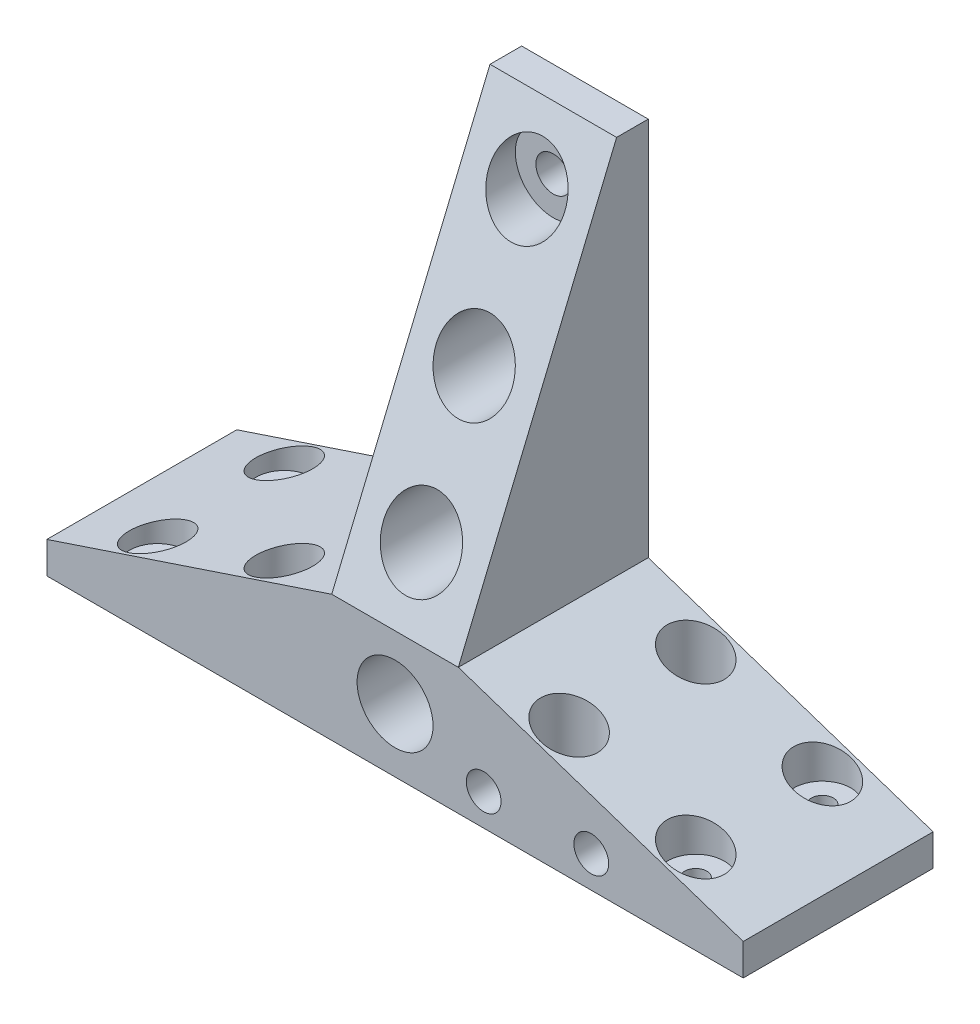
SolidWorks part; units mm, degrees
ref_plane "Plan de face" through (0, 0, 0) normal (0, 0, 1) x (1, 0, 0)
ref_plane "Plan de dessus" through (0, 0, 0) normal (0, 1, 0) x (1, 0, 0)
ref_plane "Plan de droite" through (0, 0, 0) normal (1, 0, 0) x (0, 0, -1)
sketch "Esquisse1" plane through (0, 0, 0) normal (0, 0, 1) x (1, 0, 0)
  line L1 (-9.5845, 32.7642) -> (10.4155, 32.7642)
  line L2 (-9.5845, 32.7642) -> (-9.5845, -47.2358)
  line L3 (-9.5845, -47.2358) -> (10.4155, -47.2358)
  line L4 (10.4155, 32.7642) -> (10.4155, -47.2358)
  circle A0 centre (0.4155, 22.7642) radius 2.75
  circle A1 centre (0.4155, -17.2358) radius 2.75
  circle A2 centre (0.4155, 2.7642) radius 2.75
  circle A3 centre (0.4155, -37.2358) radius 2.75
  point P13 (0.4155, -47.2358)
  dimension "D3" = 5.5
  dimension "D1" = 20
  dimension "D2" = 80
  dimension "D4" = 10
  dimension "D5" = 20
  dimension "D6" = 10
  dimension "D7" = 20
extrude "Boss.-Extru.1" add sketch "Esquisse1" along normal blind 5
sketch "Esquisse3" plane through (0, 0, 5) normal (0, 0, 1) x (1, 0, 0)
  line L0 (-9.5845, -47.2358) -> (-54.5845, -47.2358)
  line L1 (-54.5845, -47.2358) -> (-54.5845, -42.2358)
  line L2 (-54.5845, -42.2358) -> (-9.5845, -27.2358)
  line L3 (-9.5845, 32.7642) -> (-9.5845, -47.2358) construction
  line L4 (-9.5845, -27.2358) -> (-9.5845, -47.2358)
  line L5 (10.4155, -47.2358) -> (55.4155, -47.2358)
  line L6 (55.4155, -47.2358) -> (55.4155, -42.2358)
  line L7 (55.4155, -42.2358) -> (10.4155, -27.2358)
  line L8 (10.4155, -47.2358) -> (10.4155, 32.7642) construction
  line L9 (10.4155, -27.2358) -> (10.4155, -47.2358)
  dimension "D1" = 5
  dimension "D2" = 45
  dimension "D3" = 20
extrude "Boss.-Extru.2" add sketch "Esquisse3" against normal blind 5
sketch "Esquisse4" plane through (0, 0, 5) normal (0, 0, 1) x (1, 0, 0)
  line L0 (55.4155, -47.2358) -> (55.4155, -42.2358) construction
  line L1 (55.4155, -42.2358) -> (10.4155, -27.2358) construction
  line L2 (-9.5845, -27.2358) -> (-54.5845, -42.2358) construction
  line L3 (-54.5845, -42.2358) -> (-54.5845, -47.2358) construction
  line L4 (-54.5845, -47.2358) -> (55.4155, -47.2358) construction
  line L5 (55.4155, -47.2358) -> (55.4155, -42.2358)
  line L6 (55.4155, -42.2358) -> (10.4155, -27.2358)
  line L7 (-9.5845, -27.2358) -> (-54.5845, -42.2358)
  line L8 (-54.5845, -42.2358) -> (-54.5845, -47.2358)
  line L9 (-54.5845, -47.2358) -> (55.4155, -47.2358)
  line L10 (-9.5845, -27.2358) -> (10.4155, -27.2358)
  circle A0 centre (0.4155, -37.2358) radius 2.75 construction
  circle A1 centre (0.4155, -37.2358) radius 2.75
extrude "Boss.-Extru.3" add sketch "Esquisse4" along normal blind 25
sketch "Esquisse5" plane through (-9.5845, 0, 0) normal (-1, 0, 0) x (0, 0, 1)
  line L0 (5, -27.2358) -> (30, -27.2358)
  line L1 (30, -27.2358) -> (5, 32.7642)
  line L2 (5, 32.7642) -> (5, -27.2358)
extrude "Boss.-Extru.4" add sketch "Esquisse5" against normal up to surface (20 mm away) up to face at (10.4155, 2.7642, 2.5)
sketch "Esquisse6" plane through (0, 0, 5) normal (0, 0, -1) x (-1, 0, 0)
  circle A0 centre (-0.4155, 2.7642) radius 6
  circle A1 centre (-0.4155, -17.2358) radius 6
  circle A2 centre (-0.4155, 22.7642) radius 6
  circle A3 centre (-0.4155, -37.2358) radius 6
  dimension "D1" = 12
extrude "Enlèv. mat.-Extru.1" cut sketch "Esquisse6" against normal up to next
sketch "Esquisse7" plane through (0, -47.2358, 0) normal (0, -1, 0) x (1, 0, 0)
  line L0 (-42.0845, 25) -> (-22.0845, 25) construction
  line L1 (-22.0845, 25) -> (-22.0845, 5) construction
  line L2 (-54.5845, 0) -> (-54.5845, 30) construction
  line L3 (22.9155, 5) -> (22.9155, 25) construction
  line L4 (22.9155, 25) -> (42.9155, 25) construction
  line L5 (55.4155, 0) -> (55.4155, 30) construction
  circle A0 centre (-42.0845, 25) radius 1.75
  circle A1 centre (-22.0845, 25) radius 1.75
  circle A2 centre (-22.0845, 5) radius 1.75
  circle A3 centre (-42.0845, 5) radius 1.75
  circle A4 centre (42.9155, 25) radius 1.75
  circle A5 centre (42.9155, 5) radius 1.75
  circle A6 centre (22.9155, 5) radius 1.75
  circle A7 centre (22.9155, 25) radius 1.75
  point P8 (-22.0845, 15)
  point P11 (-54.5845, 15)
  point P12 (-32.0845, 25)
  point P21 (22.9155, 15)
  point P24 (55.4155, 15)
  point P25 (32.9155, 25)
  dimension "D1" = 3.5
  dimension "D4" = 3.5
  dimension "D2" = 20
  dimension "D3" = 22.5
  dimension "D5" = 20
  dimension "D6" = 22.5
extrude "Enlèv. mat.-Extru.2" cut sketch "Esquisse7" against normal up to next
ref_plane "Plan3" through (0, -42.2358, 0) normal (0, -1, 0) x (-1, 0, 0)
sketch "Esquisse9" plane through (0, -42.2358, 0) normal (0, -1, 0) x (-1, 0, 0)
  circle A0 centre (42.0845, -25) radius 4.5
  circle A1 centre (22.0845, -25) radius 4.5
  circle A2 centre (22.0845, -5) radius 4.5
  circle A3 centre (42.0845, -5) radius 4.5
  circle A4 centre (-22.9155, -25) radius 4.5
  circle A5 centre (-42.9155, -25) radius 4.5
  circle A6 centre (-42.9155, -5) radius 4.5
  circle A7 centre (-22.9155, -5) radius 4.5
  dimension "D1" = 9
extrude "Enlèv. mat.-Extru.3" cut sketch "Esquisse9" against normal up to next
sketch "Esquisse10" plane through (0, 0, 30) normal (0, 0, 1) x (1, 0, 0)
  line L0 (24.6655, -42.2358) -> (21.1655, -42.2358) construction
  line L1 (24.6655, -42.2358) -> (21.1655, -42.2358) construction
  line L2 (31.4155, -42.2358) -> (14.4155, -42.2358) construction
  circle A0 centre (14.4155, -42.2358) radius 2.75
  circle A1 centre (31.4155, -42.2358) radius 2.75
  point P6 (27.0516, -40.2138)
  point P7 (22.9155, -42.2358)
  point P8 (22.9155, -42.2358)
  dimension "D1" = 5.5
  dimension "D2" = 17
extrude "Enlèv. mat.-Extru.4" cut sketch "Esquisse10" against normal up to next
